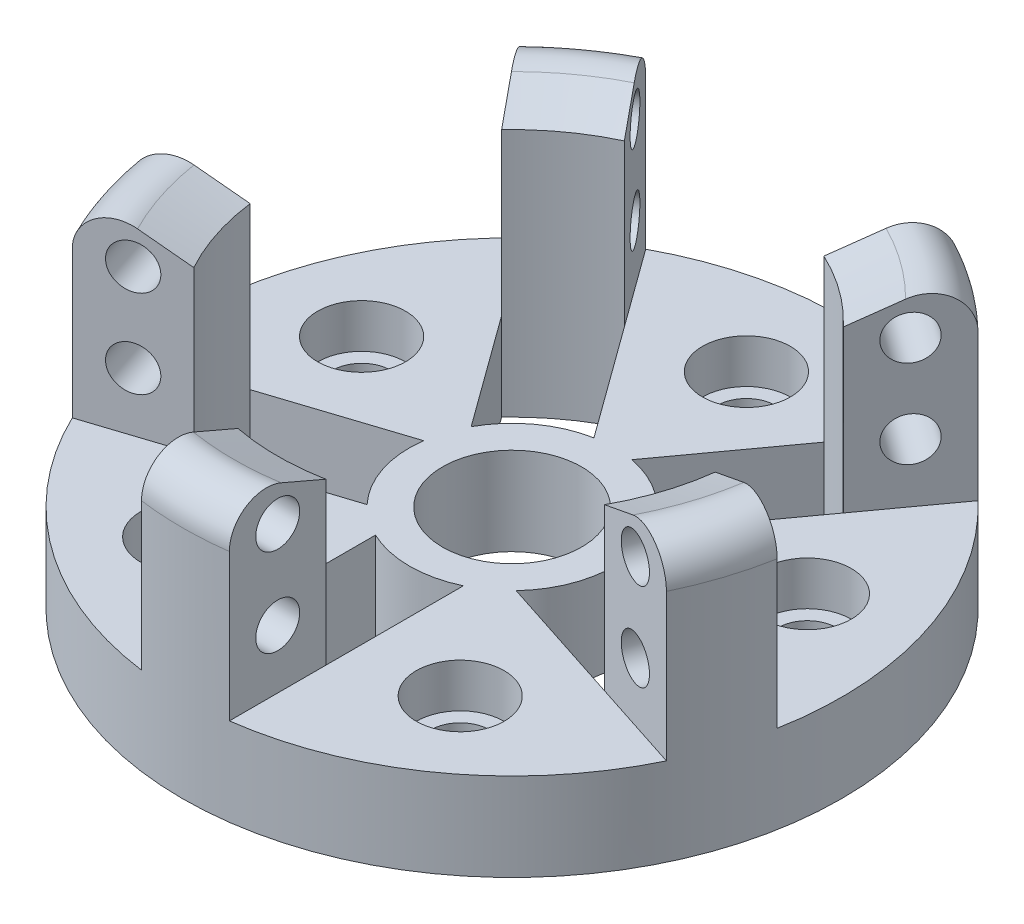
SolidWorks part; units mm, degrees
ref_plane "前视基准面" through (0, 0, 0) normal (0, 0, 1) x (1, 0, 0)
ref_plane "上视基准面" through (0, 0, 0) normal (0, 1, 0) x (1, 0, 0)
ref_plane "右视基准面" through (0, 0, 0) normal (1, 0, 0) x (0, 0, -1)
sketch "草图1" plane through (0, 0, 0) normal (0, 0, 1) x (1, 0, 0)
  line L0 (0, 0) -> (-45, 0)
  line L2 (-32, 34) -> (-32, 12)
  line L3 (-32, 12) -> (0, 12)
  line L4 (0, 12) -> (0, 0)
  line L5 (-45, 0) -> (-45, 11.036)
  line L6 (-45, 11.036) -> (-45, 32.036)
  line L7 (-32, 34) -> (-38, 36.6186)
  arc A1 (-38, 36.6186) -> (-45, 32.036) centre (-40, 32.036) ccw
  dimension "D2" = 5
  dimension "D6" = 32
  dimension "D1" = 12
  dimension "D3" = 22
  dimension "D4" = 21
  dimension "D5" = 45
  dimension "D7" = 38
revolve "旋转1" add sketch "草图1" angle 360 about L4
sketch "草图2" plane through (0, 12, 0) normal (0, 1, 0) x (1, 0, 0)
  line L0 (0, 0) -> (0, -50.4033) construction
  line L1 (0, 0) -> (-47.9364, -15.5755) construction
  line L2 (6, -12.6491) -> (6, -44.5982)
  line L3 (0, 0) -> (-29.6263, 40.7772) construction
  line L4 (0, 0) -> (29.6263, 40.7772) construction
  line L5 (0, 0) -> (47.9364, -15.5755) construction
  line L6 (-6, -12.6491) -> (-6, -44.5982)
  line L7 (-13.8841, 1.7975) -> (-44.2695, -8.0753)
  line L8 (-10.1759, -9.6151) -> (-40.5613, -19.4879)
  line L9 (-2.5809, 13.7601) -> (-21.3601, 39.6074)
  line L10 (-12.2891, 6.7066) -> (-31.0683, 32.554)
  line L11 (12.2891, 6.7066) -> (31.0683, 32.554)
  line L12 (2.5809, 13.7601) -> (21.3601, 39.6074)
  line L13 (10.1759, -9.6151) -> (40.5613, -19.4879)
  line L14 (13.8841, 1.7975) -> (44.2695, -8.0753)
  arc A0 (-12.2891, 6.7066) -> (-13.8841, 1.7975) centre (0, 0) ccw
  circle A1 centre (0, 0) radius 45 construction
  arc A2 (21.3601, 39.6074) -> (-21.3601, 39.6074) centre (0, 0) ccw
  arc A3 (-10.1759, -9.6151) -> (-6, -12.6491) centre (0, 0) ccw
  arc A4 (6, -12.6491) -> (10.1759, -9.6151) centre (0, 0) ccw
  arc A5 (13.8841, 1.7975) -> (12.2891, 6.7066) centre (0, 0) ccw
  arc A6 (2.5809, 13.7601) -> (-2.5809, 13.7601) centre (0, 0) ccw
  arc A7 (-31.0683, 32.554) -> (-44.2695, -8.0753) centre (0, 0) ccw
  arc A8 (-40.5613, -19.4879) -> (-6, -44.5982) centre (0, 0) ccw
  arc A9 (6, -44.5982) -> (40.5613, -19.4879) centre (0, 0) ccw
  arc A10 (44.2695, -8.0753) -> (29.9268, 33.6063) centre (0, 0) ccw
  point P15 (0, 0)
  point P34 (0, 0)
  circle M1 centre (0, 0) radius 32
  dimension "D1" = 28
  dimension "D2" = 5
  dimension "D3" = 6
  dimension "D4" = 5
extrude "切除-拉伸2" cut sketch "草图2" along normal through all contours A0 L10 L7 M1 | A6 L12 L9 M1 | A5 L14 L11 M1 | A4 L2 L13 M1 | A3 L8 L6 M1 | L2 A9 L13 M1 | L14 A10 L11 M1 | L12 A2 L9 M1 | L10 A7 L7 M1 | L8 A8 L6 M1
sketch "草图3" plane through (0, 12, 0) normal (0, 1, 0) x (1, 0, 0)
  line L0 (0, 0) -> (0, 35.3631) construction
  circle A0 centre (0, 0) radius 32 construction
  circle A1 centre (0, 32) radius 6
  circle A2 centre (0, 32) radius 4
  dimension "D1" = 64
  dimension "D2" = 12
  dimension "D3" = 8
extrude "切除-拉伸3" cut sketch "草图3" against normal blind 6
sketch "草图7" plane through (0, 12, 0) normal (0, 1, 0) x (1, 0, 0)
  circle A0 centre (0, 32) radius 4
extrude "切除-拉伸5" cut sketch "草图7" against normal through all
pattern_circular "阵列(圆周)2" count 5 over 360 about axis through (0, 0, 0) along (0, 1, 0) of "切除-拉伸3", "切除-拉伸5"
sketch "草图8" plane through (0, 12, 0) normal (0, 1, 0) x (1, 0, 0)
  circle A0 centre (0, 0) radius 9.5
  dimension "D1" = 19
extrude "切除-拉伸6" cut sketch "草图8" against normal through all
sketch "草图9" plane through (0, 12, 0) normal (0, 1, 0) x (1, 0, 0)
  line L0 (-6, -31.4325) -> (-6, -12.6491)
  line L1 (6, -31.4325) -> (6, -12.6491)
  circle A0 centre (0, 0) radius 14
  arc A1 (-6, -31.4325) -> (6, -31.4325) centre (0, 0) ccw construction
  arc A3 (-6, -31.4325) -> (6, -31.4325) centre (0, 0) ccw
  arc M7 (-6, -31.4325) -> (6, -31.4325) centre (0, 0) ccw
  dimension "D1" = 28
extrude "切除-拉伸7" cut sketch "草图9" against normal through all contours A0 L0 L1 M7
pattern_circular "阵列(圆周)4" count 5 over 360 about axis through (0, 0, 0) along (0, 1, 0) of "切除-拉伸7"
sketch "草图10" plane through (1.8541, 0, 5.7063) normal (0.309, 0, 0.9511) x (0.9511, 0, -0.309)
  line L0 (-45, 0) -> (45, 0) construction
  circle A0 centre (-38, 32) radius 3
  circle A1 centre (-38, 20) radius 3
  point P4 (0, 0)
  point P7 (-38, 32)
  point P8 (-38, 20)
  point P9 (0, 0)
  point P10 (0, 0)
  point P11 (0, 0)
  point P13 (0, 0)
  dimension "D1" = 6
  dimension "D2" = 12
  dimension "D3" = 20
  dimension "D4" = 38
  dimension "D5" = 38
extrude "切除-拉伸10" cut sketch "草图10" against normal through all contours A1 | A0
pattern_circular "阵列(圆周)5" count 5 over 360 about axis through (0, 12, 0) along (0, 1, 0) of "切除-拉伸10"
